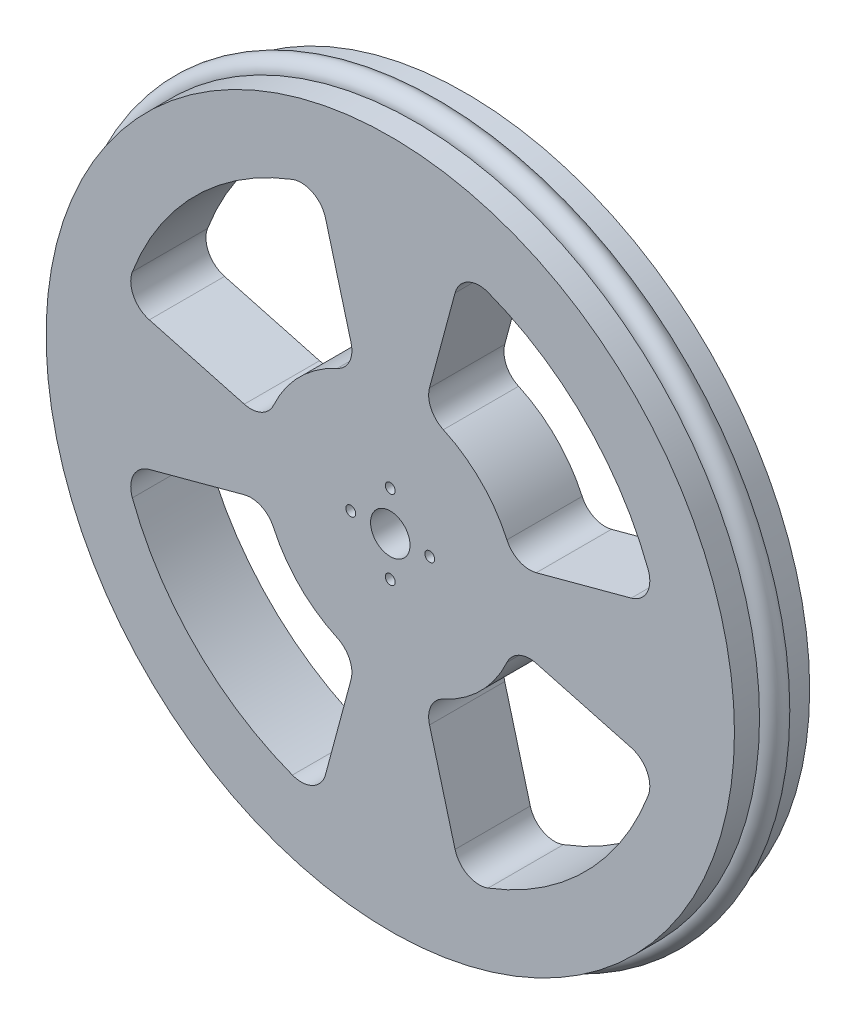
SolidWorks part; units mm, degrees
ref_plane "Front Plane" through (0, 0, 0) normal (0, 0, 1) x (1, 0, 0)
ref_plane "Top Plane" through (0, 0, 0) normal (0, 1, 0) x (1, 0, 0)
ref_plane "Right Plane" through (0, 0, 0) normal (1, 0, 0) x (0, 0, -1)
sketch "Sketch1" plane through (0, 0, 0) normal (0, 0, 1) x (1, 0, 0)
  circle A0 centre (0, 0) radius 4
  circle A1 centre (0, 0) radius 63.5
  dimension "D1" = 8
  dimension "D2" = 127
extrude "Boss-Extrude1" add sketch "Sketch1" along normal blind 5.08
sketch "Sketch2" plane through (0, 0, 5.08) normal (0, 0, 1) x (1, 0, 0)
  circle A0 centre (0, 0) radius 69.7208
  circle A1 centre (0, 0) radius 4
extrude "Boss-Extrude2" add sketch "Sketch2" along normal blind 5.08
sketch "Sketch3" plane through (0, 0, 0) normal (0, 0, -1) x (-1, 0, 0)
  circle A0 centre (0, 0) radius 4
ref_plane "Plane1" through (0, 0, 2.54) normal (0, 0, -1) x (-1, 0, 0)
mirror "Mirror1" about plane through (0, 0, 2.54) normal (0, 0, -1) of "Boss-Extrude2"
sketch "Sketch4" plane through (0, 0, -5.08) normal (0, 0, -1) x (-1, 0, 0)
  line L0 (0, 11) -> (0, 9) construction
  circle A2 centre (0, 8) radius 1
  circle A3 centre (8, 0) radius 1
  circle A4 centre (0, -8) radius 1
  circle A5 centre (-8, 0) radius 1
  point P14 (0, 0)
  dimension "D1" = 2
  dimension "D2" = 2
extrude "Cut-Extrude1" cut sketch "Sketch4" against normal through all
sketch "Sketch5" plane through (0, 0, 0) normal (1, 0, 0) x (0, 0, -1)
  line L0 (-2.54, 63.5) -> (0, 63.5)
  line L1 (0, 63.5) -> (-5.08, 63.5) construction
  line L2 (0, 69.7208) -> (0, -69.7208) construction
  line L3 (0, 63.5) -> (0, 69.7208)
  line L5 (-5.08, 69.7208) -> (-5.08, 63.5)
  line L6 (-5.08, 63.5) -> (-2.54, 63.5)
  arc A0 (0, 69.7208) -> (-5.08, 69.7208) centre (-2.54, 69.7208) ccw
revolve "Revolve1" add sketch "Sketch5" angle 360 about axis through (0, 0, 5.08) along (0, 0, -1)
sketch "Sketch6" plane through (0, 0, -5.08) normal (0, 0, -1) x (-1, 0, 0)
  line L0 (29.5715, -7.9484) -> (48.8119, -13.12)
  line L1 (13.12, 48.8119) -> (7.9484, 29.5715)
  line L2 (0, 0) -> (46.116, 46.116) construction
  line L3 (29.5715, 7.9484) -> (48.8119, 13.12)
  line L4 (7.9484, -29.5715) -> (13.12, -48.8119)
  line L5 (-7.9484, -29.5715) -> (-13.12, -48.8119)
  line L6 (-29.5715, -7.9484) -> (-48.8119, -13.12)
  line L7 (-29.5715, 7.9484) -> (-48.8119, 13.12)
  line L8 (-7.9484, 29.5715) -> (-13.12, 48.8119)
  arc A0 (52.2427, 19.8285) -> (19.8285, 52.2427) centre (0, 0) ccw
  arc A1 (23.6289, 10.7505) -> (10.7505, 23.6289) centre (0, 0) ccw
  arc A2 (48.8119, 13.12) -> (52.2427, 19.8285) centre (47.4933, 18.0259) ccw
  arc A3 (29.5715, 7.9484) -> (23.6289, 10.7505) centre (28.2528, 12.8543) cw
  arc A4 (7.9484, 29.5715) -> (10.7505, 23.6289) centre (12.8543, 28.2528) ccw
  arc A5 (13.12, 48.8119) -> (19.8285, 52.2427) centre (18.0259, 47.4933) cw
  arc A6 (48.8119, -13.12) -> (52.2427, -19.8285) centre (47.4933, -18.0259) cw
  arc A7 (19.8285, -52.2427) -> (52.2427, -19.8285) centre (0, 0) ccw
  arc A8 (13.12, -48.8119) -> (19.8285, -52.2427) centre (18.0259, -47.4933) ccw
  arc A9 (7.9484, -29.5715) -> (10.7505, -23.6289) centre (12.8543, -28.2528) cw
  arc A10 (10.7505, -23.6289) -> (23.6289, -10.7505) centre (0, 0) ccw
  arc A11 (29.5715, -7.9484) -> (23.6289, -10.7505) centre (28.2528, -12.8543) ccw
  arc A12 (-13.12, -48.8119) -> (-19.8285, -52.2427) centre (-18.0259, -47.4933) cw
  arc A13 (-52.2427, -19.8285) -> (-19.8285, -52.2427) centre (0, 0) ccw
  arc A14 (-48.8119, -13.12) -> (-52.2427, -19.8285) centre (-47.4933, -18.0259) ccw
  arc A15 (-29.5715, -7.9484) -> (-23.6289, -10.7505) centre (-28.2528, -12.8543) cw
  arc A16 (-23.6289, -10.7505) -> (-10.7505, -23.6289) centre (0, 0) ccw
  arc A17 (-7.9484, -29.5715) -> (-10.7505, -23.6289) centre (-12.8543, -28.2528) ccw
  arc A18 (-48.8119, 13.12) -> (-52.2427, 19.8285) centre (-47.4933, 18.0259) cw
  arc A19 (-19.8285, 52.2427) -> (-52.2427, 19.8285) centre (0, 0) ccw
  arc A20 (-13.12, 48.8119) -> (-19.8285, 52.2427) centre (-18.0259, 47.4933) ccw
  arc A21 (-7.9484, 29.5715) -> (-10.7505, 23.6289) centre (-12.8543, 28.2528) cw
  arc A22 (-10.7505, 23.6289) -> (-23.6289, 10.7505) centre (0, 0) ccw
  arc A23 (-29.5715, 7.9484) -> (-23.6289, 10.7505) centre (-28.2528, 12.8543) ccw
  point P4 (53.9637, 14.5047)
  point P12 (25.0698, 6.7384)
  point P15 (6.7384, 25.0698)
  point P18 (14.5047, 53.9637)
  point P58 (0, 0)
  dimension "D1" = 5.08
  dimension "D2" = 4
extrude "Cut-Extrude2" cut sketch "Sketch6" against normal through all contours L5 A17 A16 A15 L6 A14 A13 A12 | L7 A23 A22 A21 L8 A20 A19 A18 | A1 L2 A0 A5 L1 A4 | L2 A1 A3 L3 A2 A0 | L0 A11 A10 A9 L4 A8 A7 A6
